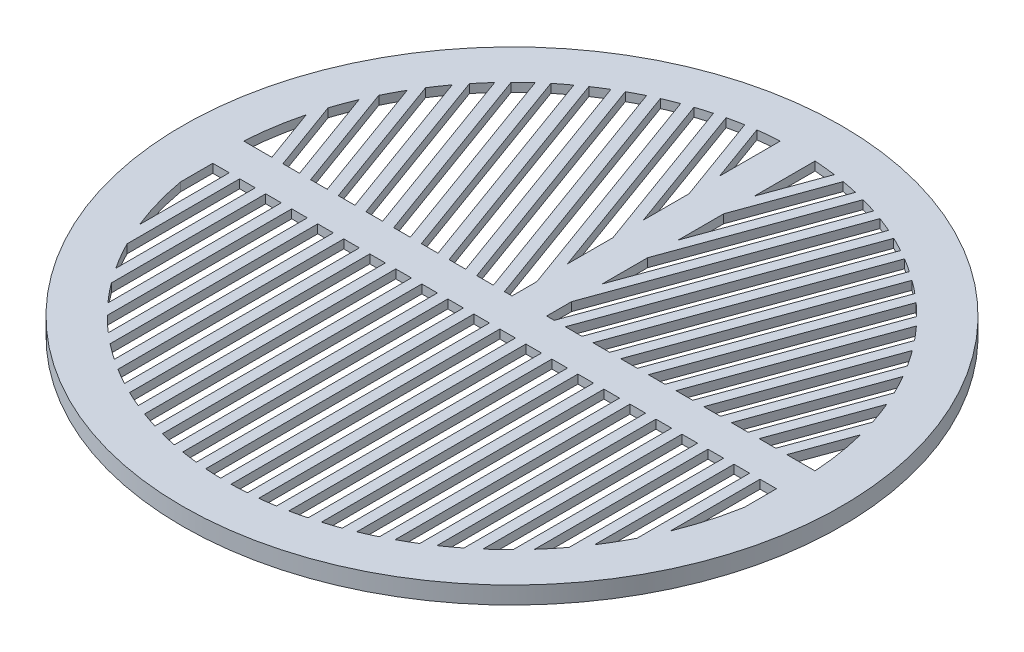
SolidWorks part; units mm, degrees
ref_plane "Front Plane" through (0, 0, 0) normal (0, 0, 1) x (1, 0, 0)
ref_plane "Top Plane" through (0, 0, 0) normal (0, 1, 0) x (1, 0, 0)
ref_plane "Right Plane" through (0, 0, 0) normal (1, 0, 0) x (0, 0, -1)
sketch "Sketch1" plane through (0, 0, 0) normal (0, 1, 0) x (1, 0, 0)
  line L1 (33, 0) -> (-33, 0) construction
  line L2 (0, 0) -> (0, 33) construction
  line L3 (2, 2) -> (2, 32.9393)
  line L4 (32.9393, 2) -> (2, 2)
  line L5 (-2, 2) -> (-2, 32.9393)
  line L6 (32.9393, -2) -> (-32.9393, -2)
  line L7 (2, 0) -> (2, 33) construction
  line L8 (-2, 2) -> (-32.9393, 2)
  line L9 (33, 2) -> (-33, 2) construction
  line L10 (-2, 0) -> (-2, 33) construction
  line L11 (33, -2) -> (-33, -2) construction
  circle A0 centre (0, 0) radius 36
  arc A1 (32.9393, 2) -> (2, 32.9393) centre (0, 0) ccw
  circle A2 centre (0, 0) radius 33 construction
  arc A3 (-32.9393, -2) -> (32.9393, -2) centre (0, 0) ccw
  arc A4 (-2, 32.9393) -> (-32.9393, 2) centre (0, 0) ccw
  dimension "D1" = 72
  dimension "D2" = 3
  dimension "D3" = 2
  dimension "D4" = 2
extrude "Boss-Extrude1" add sketch "Sketch1" along normal blind 1
sketch "Sketch2" plane through (0, 1, 0) normal (0, 1, 0) x (1, 0, 0)
  line L0 (-2, 24.1679) -> (-5.0719, 32.6079) construction
  line L1 (-2, 2) -> (-2, 32.9393) construction
  line L2 (-8.0448, 32.0044) -> (-2, 15.3965) construction
  line L3 (-25.532, 20.4045) -> (-18.908, 2.2052) construction
  line L4 (-10.9227, 31.1399) -> (-2, 6.6251) construction
  line L5 (-13.7071, 30.0186) -> (-3.5091, 2) construction
  line L6 (-32.9393, 2) -> (-2, 2) construction
  line L7 (-16.3971, 28.638) -> (-6.7017, 2) construction
  line L8 (-9.8942, 2) -> (-18.9894, 26.9889) construction
  line L9 (-21.4777, 25.0541) -> (-13.0867, 2) construction
  line L10 (-23.8518, 22.8055) -> (-16.2793, 2) construction
  line L11 (-26.0958, 20.1993) -> (-19.4718, 2) construction
  line L12 (-28.1841, 17.1655) -> (-22.6643, 2) construction
  line L13 (-25.4242, 9.5828) -> (-22.6052, 10.6088) construction
  line L14 (-22.6052, 10.6088) -> (-19.7861, 11.6349) construction
  line L15 (-19.7861, 11.6349) -> (-16.967, 12.6609) construction
  line L16 (-16.967, 12.6609) -> (-14.1479, 13.687) construction
  line L17 (-14.1479, 13.687) -> (-11.3288, 14.7131) construction
  line L18 (-11.3288, 14.7131) -> (-8.5098, 15.7391) construction
  line L19 (-8.5098, 15.7391) -> (-5.6907, 16.7652) construction
  line L20 (-5.6907, 16.7652) -> (-2.8716, 17.7912) construction
  line L21 (-2, 24.1679) -> (2, 13.178) construction
  line L22 (2, 32.9393) -> (2, 2) construction
  line L23 (-2.8716, 17.7912) -> (-0.0525, 18.8173) construction
  line L24 (-2, 32.9393) -> (-4.8191, 31.9133) construction
  line L25 (-30.0737, 13.5857) -> (-25.8569, 2) construction
  line L26 (-31.682, 9.2331) -> (-29.0494, 2) construction
  line L27 (-25.4242, 9.5828) -> (-28.2433, 8.5567) construction
  line L28 (-28.2433, 8.5567) -> (-31.0624, 7.5306) construction
  line L29 (-31.9565, 8.2329) -> (-29.6879, 2)
  line L30 (-30.4217, 12.7875) -> (-26.4954, 2)
  line L31 (-28.5798, 16.4983) -> (-23.3028, 2)
  line L32 (-26.527, 19.6296) -> (-20.1103, 2)
  line L33 (-24.3117, 22.3146) -> (-16.9178, 2)
  line L34 (-21.9621, 24.6306) -> (-13.7252, 2)
  line L35 (-9.2557, 2) -> (-18.479, 27.3409)
  line L36 (-16.9235, 28.3301) -> (-7.3402, 2)
  line L37 (-14.2527, 29.7634) -> (-4.1476, 2)
  line L38 (-11.487, 30.9362) -> (-2, 4.8708)
  line L39 (-8.6279, 31.8522) -> (-2, 13.6422)
  line L40 (-2, 25.9222) -> (-4.4656, 32.6965)
  line L41 (-31.3894, 10.1835) -> (-28.4109, 2)
  line L42 (-29.7148, 14.3538) -> (-25.2184, 2)
  line L43 (-27.7806, 17.8112) -> (-22.0258, 2)
  line L44 (-25.6585, 20.752) -> (-18.8333, 2)
  line L45 (-23.3868, 23.2821) -> (-15.6408, 2)
  line L46 (-20.9888, 25.4651) -> (-12.4482, 2)
  line L47 (-10.5327, 2) -> (-19.4957, 26.6255)
  line L48 (-15.8668, 28.9352) -> (-6.0632, 2)
  line L49 (-13.1577, 30.2634) -> (-2.8706, 2)
  line L50 (-10.3546, 31.3334) -> (-2, 8.3794)
  line L51 (-7.4579, 32.1462) -> (-2, 17.1508)
  line L52 (-2, 22.4136) -> (-5.6742, 32.5085)
  line L53 (-31.1182, 9.4383) -> (-28.4856, 2.2052) construction
  line L54 (-29.5099, 13.7909) -> (-25.2931, 2.2052) construction
  line L55 (-32.9393, 2) -> (-2, 2)
  line L56 (-2, 2) -> (-2, 32.9393)
  line L57 (-29.6879, 2) -> (-28.4109, 2)
  line L58 (-2, 4.8708) -> (-2, 8.3794)
  line L59 (-27.6203, 17.3707) -> (-22.1005, 2.2052) construction
  line L60 (-28.7479, 16.9603) -> (-23.2282, 1.7948) construction
  line L61 (-30.6375, 13.3805) -> (-26.4207, 1.7948) construction
  line L62 (-32.2458, 9.0279) -> (-29.6132, 1.7948) construction
  line L63 (-26.6596, 19.994) -> (-20.0356, 1.7948) construction
  line L64 (-24.4157, 22.6003) -> (-16.8431, 1.7948) construction
  line L65 (-23.288, 23.0107) -> (-15.7155, 2.2052) construction
  line L66 (-22.0415, 24.8489) -> (-13.6506, 1.7948) construction
  line L67 (-20.9139, 25.2593) -> (-12.5229, 2.2052) construction
  line L68 (-10.458, 1.7948) -> (-19.5532, 26.7837) construction
  line L69 (-9.3304, 2.2052) -> (-18.4256, 27.1941) construction
  line L70 (-16.9609, 28.4328) -> (-7.2655, 1.7948) construction
  line L71 (-15.8333, 28.8432) -> (-6.1379, 2.2052) construction
  line L72 (-13.1433, 30.2238) -> (-2.9453, 2.2052) construction
  line L73 (-14.2709, 29.8134) -> (-4.073, 1.7948) construction
  line L74 (-11.4865, 30.9347) -> (-2.5638, 6.4199) construction
  line L75 (-10.3589, 31.3451) -> (-1.4362, 6.8303) construction
  line L76 (-7.481, 32.2096) -> (-1.4362, 15.6017) construction
  line L77 (-8.6086, 31.7992) -> (-2.5638, 15.1913) construction
  line L78 (-2.5638, 23.9627) -> (-5.6357, 32.4027) construction
  line L79 (-1.4362, 24.3731) -> (-4.5081, 32.8131) construction
  line L80 (-26.4954, 2) -> (-25.2184, 2)
  line L81 (-23.3028, 2) -> (-22.0258, 2)
  line L82 (-20.1103, 2) -> (-18.8333, 2)
  line L83 (-16.9178, 2) -> (-15.6408, 2)
  line L84 (-13.7252, 2) -> (-12.4482, 2)
  line L85 (-10.5327, 2) -> (-9.2557, 2)
  line L86 (-7.3402, 2) -> (-6.0632, 2)
  line L87 (-4.1476, 2) -> (-2.8706, 2)
  line L88 (-2, 22.4136) -> (-2, 25.9222)
  line L89 (-2, 13.6422) -> (-2, 17.1508)
  arc A0 (-2, 32.9393) -> (-32.9393, 2) centre (0, 0) ccw construction
  arc A1 (-31.3894, 10.1835) -> (-31.9565, 8.2329) centre (0, 0) ccw
  arc A2 (-2, 32.9393) -> (-32.9393, 2) centre (0, 0) ccw
  arc A3 (-4.4656, 32.6965) -> (-5.6742, 32.5085) centre (0, 0) ccw
  arc A4 (-29.7148, 14.3538) -> (-30.4217, 12.7875) centre (0, 0) ccw
  arc A5 (-27.7806, 17.8112) -> (-28.5798, 16.4983) centre (0, 0) ccw
  arc A6 (-25.6585, 20.752) -> (-26.527, 19.6296) centre (0, 0) ccw
  arc A7 (-23.3868, 23.2821) -> (-24.3117, 22.3146) centre (0, 0) ccw
  arc A8 (-20.9888, 25.4651) -> (-21.9621, 24.6306) centre (0, 0) ccw
  arc A9 (-18.479, 27.3409) -> (-19.4957, 26.6255) centre (0, 0) ccw
  arc A10 (-15.8668, 28.9352) -> (-16.9235, 28.3301) centre (0, 0) ccw
  arc A11 (-13.1577, 30.2634) -> (-14.2527, 29.7634) centre (0, 0) ccw
  arc A12 (-10.3546, 31.3334) -> (-11.487, 30.9362) centre (0, 0) ccw
  arc A13 (-7.4579, 32.1462) -> (-8.6279, 31.8522) centre (0, 0) ccw
  dimension "D1" = 20
  dimension "D2" = 3
  dimension "D3" = 0.6
  dimension "D4" = 0.6
  dimension "D5" = 0
extrude "Boss-Extrude2" add sketch "Sketch2" against normal up to surface (1 mm away) up to face at (-14.2681, 0, -14.2681)
mirror "Mirror1" about plane through (0, 0, 0) normal (1, 0, 0) of "Boss-Extrude2"
sketch "Sketch3" plane through (0, 1, 0) normal (0, 1, 0) x (1, 0, 0)
  line L0 (0, -2) -> (0, -33) construction
  line L1 (-0.6, -2) -> (-0.6, -32.9945)
  line L2 (32.9393, -2) -> (-32.9393, -2) construction
  line L3 (3, -2) -> (3, -32.8634) construction
  line L4 (6, -2) -> (6, -32.45) construction
  line L5 (9, -2) -> (9, -31.749) construction
  line L6 (12, -2) -> (12, -30.7409) construction
  line L7 (15, -2) -> (15, -29.3939) construction
  line L8 (18, -2) -> (18, -27.6586) construction
  line L9 (21, -2) -> (21, -25.4558) construction
  line L10 (24, -2) -> (24, -22.6495) construction
  line L11 (27, -2) -> (27, -18.9737) construction
  line L12 (30, -2) -> (30, -13.7477) construction
  line L13 (18.6, -2) -> (18.6, -33) construction
  line L14 (0, -2) -> (0.6, -2) construction
  line L15 (-3, -2) -> (-3, -32.8634) construction
  line L16 (-6, -2) -> (-6, -32.45) construction
  line L17 (-9, -2) -> (-9, -31.749) construction
  line L18 (-12, -2) -> (-12, -30.7409) construction
  line L19 (-15, -2) -> (-15, -29.3939) construction
  line L20 (-18, -2) -> (-18, -27.6586) construction
  line L21 (-21, -2) -> (-21, -25.4558) construction
  line L22 (-24, -2) -> (-24, -22.6495) construction
  line L23 (-27, -2) -> (-27, -18.9737) construction
  line L24 (-30, -2) -> (-30, -13.7477) construction
  line L25 (18, -2) -> (18, -33) construction
  line L26 (0, -2) -> (-0.6, -2) construction
  line L27 (2.4, -2) -> (2.4, -32.9126)
  line L28 (5.4, -2) -> (5.4, -32.5552)
  line L29 (8.4, -2) -> (8.4, -31.913)
  line L30 (11.4, -2) -> (11.4, -30.9684)
  line L31 (14.4, -2) -> (14.4, -29.6924)
  line L32 (17.4, -2) -> (17.4, -28.04)
  line L33 (20.4, -2) -> (20.4, -25.9392)
  line L34 (23.4, -2) -> (23.4, -23.2689)
  line L35 (26.4, -2) -> (26.4, -19.8)
  line L36 (29.4, -2) -> (29.4, -14.988)
  line L37 (32.5, -2) -> (32.5, -5.7228)
  line L38 (-3.6, -2) -> (-3.6, -32.803)
  line L39 (-6.6, -2) -> (-6.6, -32.3333)
  line L40 (-9.6, -2) -> (-9.6, -31.5728)
  line L41 (-12.6, -2) -> (-12.6, -30.4998)
  line L42 (-15.6, -2) -> (-15.6, -29.0799)
  line L43 (-18.6, -2) -> (-18.6, -27.2588)
  line L44 (-21.6, -2) -> (-21.6, -24.9487)
  line L45 (-24.6, -2) -> (-24.6, -21.9964)
  line L46 (-27.6, -2) -> (-27.6, -18.0898)
  line L47 (-30.6, -2) -> (-30.6, -12.3548)
  line L48 (30.6, -2) -> (30.6, -33) construction
  line L49 (0.6, -2) -> (0.6, -32.9945)
  line L50 (3.6, -2) -> (3.6, -32.803)
  line L51 (6.6, -2) -> (6.6, -32.3333)
  line L52 (9.6, -2) -> (9.6, -31.5728)
  line L53 (12.6, -2) -> (12.6, -30.4998)
  line L54 (15.6, -2) -> (15.6, -29.0799)
  line L55 (18.6, -2) -> (18.6, -27.2588)
  line L56 (21.6, -2) -> (21.6, -24.9487)
  line L57 (24.6, -2) -> (24.6, -21.9964)
  line L58 (27.6, -2) -> (27.6, -18.0898)
  line L59 (30.6, -2) -> (30.6, -12.3548)
  line L60 (17.4, -2) -> (17.4, -33) construction
  line L61 (-2.4, -2) -> (-2.4, -32.9126)
  line L62 (-5.4, -2) -> (-5.4, -32.5552)
  line L63 (-8.4, -2) -> (-8.4, -31.913)
  line L64 (-11.4, -2) -> (-11.4, -30.9684)
  line L65 (-14.4, -2) -> (-14.4, -29.6924)
  line L66 (-17.4, -2) -> (-17.4, -28.04)
  line L67 (-20.4, -2) -> (-20.4, -25.9392)
  line L68 (-23.4, -2) -> (-23.4, -23.2689)
  line L69 (-26.4, -2) -> (-26.4, -19.8)
  line L70 (-29.4, -2) -> (-29.4, -14.988)
  line L71 (-32.5, -2) -> (-32.5, -5.7228)
  line L72 (30, -2) -> (30, -33) construction
  line L73 (32.9393, -2) -> (-32.9393, -2)
  line L74 (32.9393, -2) -> (32.5, -2)
  line L75 (-30.6, -2) -> (-30.6, -33) construction
  line L76 (-30, -2) -> (-30, -33) construction
  line L77 (-29.4, -2) -> (-29.4, -33) construction
  line L78 (-27.6, -2) -> (-27.6, -33) construction
  line L79 (-27, -2) -> (-27, -33) construction
  line L80 (-26.4, -2) -> (-26.4, -33) construction
  line L81 (-24.6, -2) -> (-24.6, -33) construction
  line L82 (-24, -2) -> (-24, -33) construction
  line L83 (-23.4, -2) -> (-23.4, -33) construction
  line L84 (-21.6, -2) -> (-21.6, -33) construction
  line L85 (-21, -2) -> (-21, -33) construction
  line L86 (-20.4, -2) -> (-20.4, -33) construction
  line L87 (-18.6, -2) -> (-18.6, -33) construction
  line L88 (-18, -2) -> (-18, -33) construction
  line L89 (-17.4, -2) -> (-17.4, -33) construction
  line L90 (-15.6, -2) -> (-15.6, -33) construction
  line L91 (-15, -2) -> (-15, -33) construction
  line L92 (-14.4, -2) -> (-14.4, -33) construction
  line L93 (-12.6, -2) -> (-12.6, -33) construction
  line L94 (-12, -2) -> (-12, -33) construction
  line L95 (-11.4, -2) -> (-11.4, -33) construction
  line L96 (-9.6, -2) -> (-9.6, -33) construction
  line L97 (-9, -2) -> (-9, -33) construction
  line L98 (-8.4, -2) -> (-8.4, -33) construction
  line L99 (29.4, -2) -> (29.4, -33) construction
  line L100 (27.6, -2) -> (27.6, -33) construction
  line L101 (27, -2) -> (27, -33) construction
  line L102 (26.4, -2) -> (26.4, -33) construction
  line L103 (24.6, -2) -> (24.6, -33) construction
  line L104 (24, -2) -> (24, -33) construction
  line L105 (23.4, -2) -> (23.4, -33) construction
  line L106 (21.6, -2) -> (21.6, -33) construction
  line L107 (21, -2) -> (21, -33) construction
  line L108 (20.4, -2) -> (20.4, -33) construction
  line L109 (15.6, -2) -> (15.6, -33) construction
  line L110 (15, -2) -> (15, -33) construction
  line L111 (14.4, -2) -> (14.4, -33) construction
  line L112 (12.6, -2) -> (12.6, -33) construction
  line L113 (12, -2) -> (12, -33) construction
  line L114 (11.4, -2) -> (11.4, -33) construction
  line L115 (9.6, -2) -> (9.6, -33) construction
  line L116 (9, -2) -> (9, -33) construction
  line L117 (8.4, -2) -> (8.4, -33) construction
  line L118 (6.6, -2) -> (6.6, -33) construction
  line L119 (6, -2) -> (6, -33) construction
  line L120 (5.4, -2) -> (5.4, -33) construction
  line L121 (3.6, -2) -> (3.6, -33) construction
  line L122 (3, -2) -> (3, -33) construction
  line L123 (2.4, -2) -> (2.4, -33) construction
  line L124 (0.6, -2) -> (0.6, -33) construction
  line L125 (-0.6, -2) -> (-0.6, -33) construction
  line L126 (-2.4, -2) -> (-2.4, -33) construction
  line L127 (-3, -2) -> (-3, -33) construction
  line L128 (-6.6, -2) -> (-6.6, -33) construction
  line L129 (-3.6, -2) -> (-3.6, -33) construction
  line L130 (-5.4, -2) -> (-5.4, -33) construction
  line L131 (-6, -2) -> (-6, -33) construction
  line L132 (-32.5, -2) -> (-32.9393, -2)
  line L133 (-29.4, -2) -> (-30.6, -2)
  line L134 (-26.4, -2) -> (-27.6, -2)
  line L135 (-23.4, -2) -> (-24.6, -2)
  line L136 (-20.4, -2) -> (-21.6, -2)
  line L137 (-17.4, -2) -> (-18.6, -2)
  line L138 (-11.4, -2) -> (-12.6, -2)
  line L139 (-14.4, -2) -> (-15.6, -2)
  line L140 (-8.4, -2) -> (-9.6, -2)
  line L141 (-5.4, -2) -> (-6.6, -2)
  line L142 (-2.4, -2) -> (-3, -2) construction
  line L143 (-2.4, -2) -> (-3.6, -2)
  line L144 (2.4, -2) -> (3, -2) construction
  line L286 (0.6, -2) -> (-0.6, -2)
  line L287 (-33, -2) -> (-33, -33) construction
  line L288 (3.6, -2) -> (2.4, -2)
  line L289 (6.6, -2) -> (5.4, -2)
  line L290 (33, -2) -> (33, -33) construction
  line L291 (9.6, -2) -> (8.4, -2)
  line L292 (12.6, -2) -> (11.4, -2)
  line L293 (15.6, -2) -> (14.4, -2)
  line L294 (18.6, -2) -> (17.4, -2)
  line L295 (21.6, -2) -> (20.4, -2)
  line L296 (24.6, -2) -> (23.4, -2)
  line L297 (27.6, -2) -> (26.4, -2)
  line L298 (30.6, -2) -> (29.4, -2)
  arc A0 (-30.6, -12.3548) -> (-29.4, -14.988) centre (0, 0) ccw
  arc A1 (-32.9393, -2) -> (32.9393, -2) centre (0, 0) ccw construction
  arc A2 (-32.9393, -2) -> (32.9393, -2) centre (0, 0) ccw
  arc A3 (-32.9393, -2) -> (-32.5, -5.7228) centre (0, 0) ccw
  arc A4 (32.5, -5.7228) -> (32.9393, -2) centre (0, 0) ccw
  arc A5 (29.4, -14.988) -> (30.6, -12.3548) centre (0, 0) ccw
  arc A6 (26.4, -19.8) -> (27.6, -18.0898) centre (0, 0) ccw
  arc A7 (23.4, -23.2689) -> (24.6, -21.9964) centre (0, 0) ccw
  arc A8 (20.4, -25.9392) -> (21.6, -24.9487) centre (0, 0) ccw
  arc A9 (17.4, -28.04) -> (18.6, -27.2588) centre (0, 0) ccw
  arc A10 (14.4, -29.6924) -> (15.6, -29.0799) centre (0, 0) ccw
  arc A11 (11.4, -30.9684) -> (12.6, -30.4998) centre (0, 0) ccw
  arc A12 (8.4, -31.913) -> (9.6, -31.5728) centre (0, 0) ccw
  arc A13 (5.4, -32.5552) -> (6.6, -32.3333) centre (0, 0) ccw
  arc A14 (2.4, -32.9126) -> (3.6, -32.803) centre (0, 0) ccw
  arc A15 (-0.6, -32.9945) -> (0.6, -32.9945) centre (0, 0) ccw
  arc A16 (-3.6, -32.803) -> (-2.4, -32.9126) centre (0, 0) ccw
  arc A17 (-12.6, -30.4998) -> (-11.4, -30.9684) centre (0, 0) ccw
  arc A18 (-6.6, -32.3333) -> (-5.4, -32.5552) centre (0, 0) ccw
  arc A19 (-9.6, -31.5728) -> (-8.4, -31.913) centre (0, 0) ccw
  arc A20 (-15.6, -29.0799) -> (-14.4, -29.6924) centre (0, 0) ccw
  arc A21 (-18.6, -27.2588) -> (-17.4, -28.04) centre (0, 0) ccw
  arc A22 (-21.6, -24.9487) -> (-20.4, -25.9392) centre (0, 0) ccw
  arc A23 (-24.6, -21.9964) -> (-23.4, -23.2689) centre (0, 0) ccw
  arc A24 (-27.6, -18.0898) -> (-26.4, -19.8) centre (0, 0) ccw
  dimension "D3" = 3
  dimension "D4" = 0.6
  dimension "D1" = 3
  dimension "D5" = 0.6
  dimension "D6" = 0
  dimension "D2" = 12
extrude "Boss-Extrude3" add sketch "Sketch3" against normal up to surface (1 mm away) up to face at (5.7465, 0, -21.3047)
sketch "Sketch4" plane through (0, 1, 0) normal (0, 1, 0) x (1, 0, 0)
  circle A1 centre (0, 0) radius 36
  circle A2 centre (0, 0) radius 36
  circle A4 centre (0, 0) radius 38
  circle A5 centre (0, 0) radius 38
  dimension "D1" = 0
  dimension "D2" = 2
extrude "Boss-Extrude4" add sketch "Sketch4" against normal blind 2
